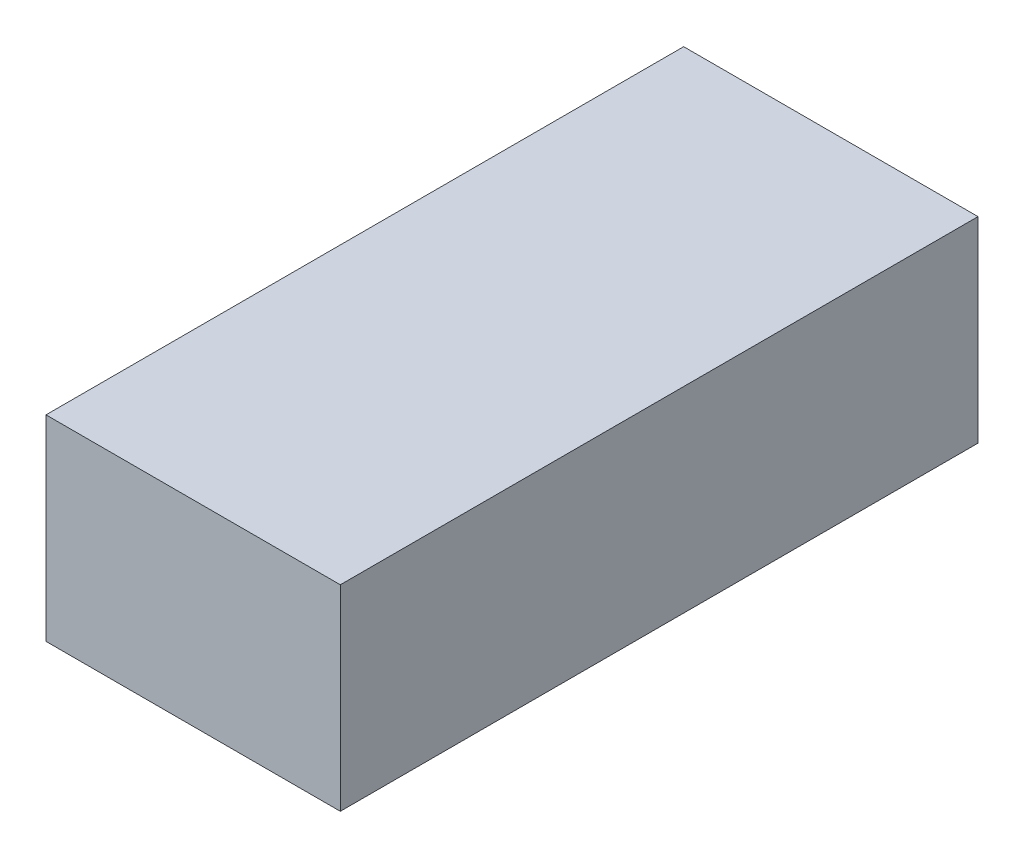
SolidWorks part; units mm, degrees
material "C (Графит)"
ref_plane "Спереди" through (0, 0, 0) normal (0, 0, 1) x (1, 0, 0)
ref_plane "Сверху" through (0, 0, 0) normal (0, 1, 0) x (1, 0, 0)
ref_plane "Справа" through (0, 0, 0) normal (1, 0, 0) x (0, 0, -1)
sketch "Эскиз1" plane through (0, 0, 0) normal (0, 0, 1) x (1, 0, 0)
  line L1 (3, 2) -> (-3, 2)
  line L2 (3, 2) -> (3, -2)
  line L3 (3, -2) -> (-3, -2)
  line L4 (-3, 2) -> (-3, -2)
  line L5 (3, 2) -> (-3, -2) construction
  line L6 (3, -2) -> (-3, 2) construction
  point P0 (0, 0)
  dimension "D1" = 4
  dimension "D2" = 6
extrude "Бобышка-Вытянуть1" add sketch "Эскиз1" along normal blind 13
